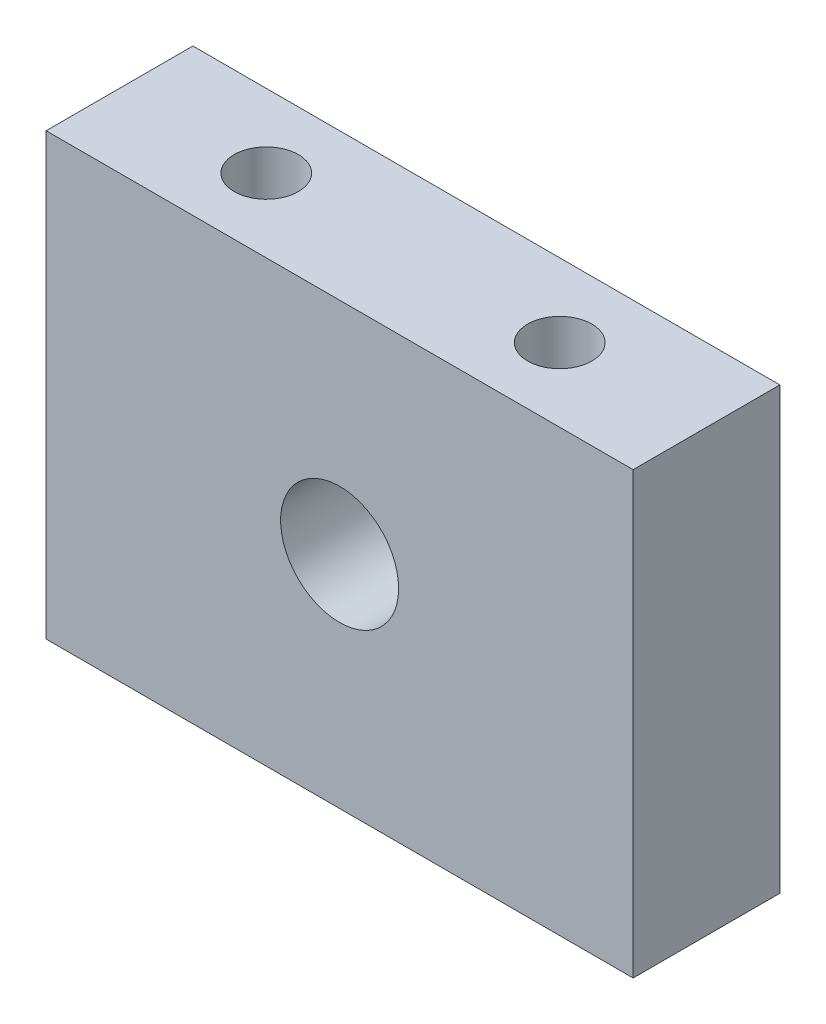
SolidWorks part; units mm, degrees
ref_plane "Front Plane" through (0, 0, 0) normal (0, 0, 1) x (1, 0, 0)
ref_plane "Top Plane" through (0, 0, 0) normal (0, 1, 0) x (1, 0, 0)
ref_plane "Right Plane" through (0, 0, 0) normal (1, 0, 0) x (0, 0, -1)
sketch "Sketch1" plane through (0, 0, 0) normal (0, 0, 1) x (1, 0, 0)
  line L1 (-12.7, 9.525) -> (12.7, 9.525)
  line L2 (-12.7, 9.525) -> (-12.7, -9.525)
  line L3 (-12.7, -9.525) -> (12.7, -9.525)
  line L4 (12.7, 9.525) -> (12.7, -9.525)
  line L5 (-12.7, 9.525) -> (12.7, -9.525) construction
  line L6 (-12.7, -9.525) -> (12.7, 9.525) construction
  point P0 (0, 0)
  dimension "D1" = 19.05
  dimension "D2" = 25.4
extrude "Boss-Extrude1" add sketch "Sketch1" along normal mid plane 6.35
sketch "Sketch2" plane through (0, 0, 3.175) normal (0, 0, 1) x (1, 0, 0)
  circle A0 centre (0, 0) radius 2.5527
  dimension "D1" = 5.1054
extrude "Cut-Extrude1" cut sketch "Sketch2" against normal through all
sketch "Sketch4" plane through (0, 9.525, 0) normal (0, 1, 0) x (1, 0, 0)
  line L0 (-12.7, -3.175) -> (-12.7, 3.175) construction
  line L1 (0, -3.7251) -> (0, 5.0748) construction
  circle A0 centre (-6.35, 0) radius 1.3891
  circle A1 centre (6.35, 0) radius 1.3891
  point P2 (-12.7, 0)
  dimension "D1" = 2.7781
  dimension "D2" = 6.35
extrude "Cut-Extrude2" cut sketch "Sketch4" against normal blind 6.35
sketch "Sketch5" plane through (0, -9.525, 0) normal (0, -1, 0) x (1, 0, 0)
  line L0 (12.7, 3.175) -> (12.7, -3.175) construction
  line L1 (0, -3.175) -> (0, 3.175) construction
  line L2 (-12.7, -3.175) -> (12.7, -3.175) construction
  line L3 (-12.7, 3.175) -> (12.7, 3.175) construction
  circle A0 centre (6.35, 0) radius 1.3891
  circle A1 centre (-6.35, 0) radius 1.3891
  point P2 (12.7, 0)
  dimension "D1" = 6.35
  dimension "D2" = 2.7781
extrude "Cut-Extrude3" cut sketch "Sketch5" against normal blind 6.35
